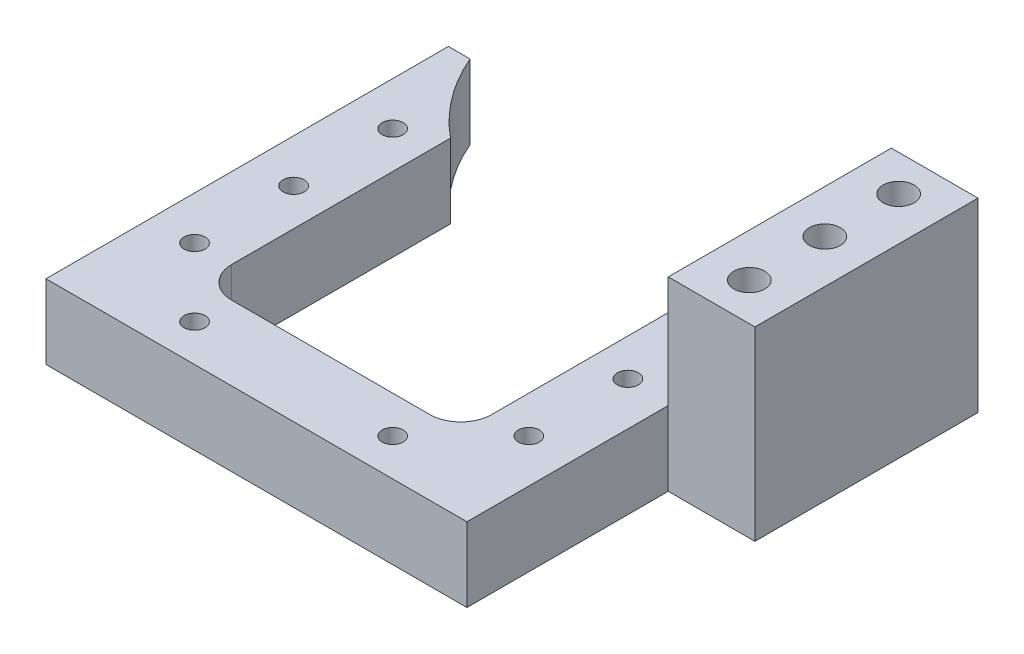
SolidWorks part; units mm, degrees
ref_plane "Front Plane" through (0, 0, 0) normal (0, 0, 1) x (1, 0, 0)
ref_plane "Top Plane" through (0, 0, 0) normal (0, 1, 0) x (1, 0, 0)
ref_plane "Right Plane" through (0, 0, 0) normal (1, 0, 0) x (0, 0, -1)
sketch "Sketch1" plane through (0, 0, 0) normal (0, 1, 0) x (1, 0, 0)
  line L0 (0, 0) -> (0, 11.5) construction
  line L1 (0, 0) -> (0, -36) construction
  line L2 (0, 0) -> (13.5, 0) construction
  line L3 (0, 0) -> (-13.5, 0) construction
  line L4 (-13.5, 0) -> (-13.5, -6.5) construction
  line L5 (-13.5, -6.5) -> (-13.5, -14.5) construction
  line L6 (-13.5, -14.5) -> (-13.5, -22.5) construction
  line L7 (-13.5, -22.5) -> (-13.5, -30.5) construction
  line L8 (-17, -6.5) -> (-17, -33.5)
  line L9 (-17, -33.5) -> (-17, -39)
  line L12 (-13.5, -30.5) -> (-13.5, -36) construction
  line L13 (-13.5, -36) -> (-8, -36) construction
  line L14 (13.5, 0) -> (13.5, -6.5) construction
  line L15 (13.5, -6.5) -> (13.5, -14.5) construction
  line L16 (13.5, -14.5) -> (13.5, -22.5) construction
  line L17 (13.5, -22.5) -> (13.5, -30.5) construction
  line L18 (13.5, -30.5) -> (13.5, -36) construction
  line L19 (13.5, -36) -> (8, -36) construction
  line L20 (-13.5, -6.5) -> (-17, -6.5) construction
  line L21 (-13.5, -6.5) -> (-10, -6.5) construction
  line L22 (13.5, -6.5) -> (10, -6.5) construction
  line L23 (13.5, -6.5) -> (17, -6.5) construction
  line L24 (17, -33.5) -> (17, -39)
  line L25 (17, -6.5) -> (17, -33.5)
  line L26 (13.5, -6.5) -> (17, -6.5) construction
  line L27 (-17, -39) -> (17, -39)
  line L28 (-17, -6.5) -> (-15.25, -6.5)
  line L29 (-10.5, -12.8282) -> (-10.5, -30.5)
  line L30 (-10.5, -30.5) -> (-8, -30.5)
  line L31 (-8, -30.5) -> (-8, -33)
  line L32 (8, -33) -> (-8, -33)
  line L33 (8, -30.5) -> (8, -33)
  line L34 (10.5, -30.5) -> (8, -30.5)
  line L35 (10.5, -12.8282) -> (10.5, -30.5)
  line L36 (17, -6.5) -> (15.25, -6.5)
  circle A0 centre (0, 0) radius 16 construction
  circle A1 centre (0, 0) radius 11 construction
  circle A2 centre (-13.5, -30.5) radius 0.85
  circle A3 centre (-13.5, -22.5) radius 0.85
  circle A4 centre (-13.5, -14.5) radius 0.85
  circle A5 centre (-8, -36) radius 0.85
  circle A6 centre (8, -36) radius 0.85
  circle A7 centre (13.5, -30.5) radius 0.85
  circle A8 centre (13.5, -22.5) radius 0.85
  circle A9 centre (13.5, -14.5) radius 0.85
  arc A10 (-15.25, -6.5) -> (-10.5, -12.8282) centre (0, 0) ccw
  arc A11 (15.25, -6.5) -> (10.5, -12.8282) centre (0, 0) cw
  point P45 (0, -33.5)
  dimension "D1" = 32
  dimension "D2" = 22
  dimension "D3" = 11.5
  dimension "D13" = 1.7
  dimension "D14" = 2.5
  dimension "D4" = 36
  dimension "D5" = 3
  dimension "D6" = 13.5
  dimension "D7" = 6.5
  dimension "D8" = 8
  dimension "D9" = 8
  dimension "D10" = 8
  dimension "D11" = 5.5
  dimension "D12" = 5.5
  dimension "D15" = 3.5
  dimension "D16" = 3.5
  dimension "D17" = 3.5
  dimension "D18" = 3
  dimension "D19" = 13.5
  dimension "D20" = 3
extrude "Boss-Extrude1" add sketch "Sketch1" along normal blind 6
sketch "Sketch2" plane through (0, 0, 0) normal (0, -1, 0) x (1, 0, 0)
  line L0 (10.5, 12.8282) -> (10.5, 17.3382) construction
  line L1 (10.5, 12.8282) -> (10.5, 30.5) construction
  line L2 (10.5, 17.3382) -> (10.5, 19.3382) construction
  circle A0 centre (10.5, 19.3382) radius 2
  dimension "D3" = 4
  dimension "D1" = 4.51
  dimension "D2" = 2
sketch "Sketch3" plane through (0, 0, 0) normal (0, -1, 0) x (1, 0, 0)
  line L0 (17, 22.74) -> (24, 22.74)
  line L3 (24, 22.74) -> (24, 4.72)
  line L4 (24, 4.72) -> (17, 4.72)
  line L5 (17, 4.72) -> (17, 7.9018)
  line L6 (17, 22.74) -> (17, 7.9018)
  dimension "D1" = 16.26
  dimension "D2" = 7
  dimension "D3" = 18.02
extrude "Boss-Extrude2" add sketch "Sketch3" against normal blind 15
sketch "Sketch4" plane through (0, 0, 0) normal (0, -1, 0) x (1, 0, 0)
  line L0 (17, 22.74) -> (17, 10.54) construction
  line L1 (17, 10.54) -> (24, 10.54) construction
  line L2 (24, 4.72) -> (24, 22.74) construction
  line L3 (24, 4.72) -> (24, 22.74) construction
  line L4 (17, 10.54) -> (17, 4.72) construction
  line L5 (24, 4.72) -> (17, 10.54) construction
  line L6 (24, 10.54) -> (17, 4.72) construction
  line L9 (24, 16.64) -> (17, 16.64) construction
  line L10 (24, 10.54) -> (17, 16.64) construction
  line L11 (17, 10.54) -> (24, 16.64) construction
  line L12 (24, 16.64) -> (17, 22.74) construction
  line L13 (17, 16.64) -> (24, 22.74) construction
  circle A0 centre (20.5, 7.63) radius 1.25
  circle A1 centre (20.5, 13.59) radius 1.25
  circle A2 centre (20.5, 19.69) radius 1.25
  dimension "D1" = 12.2
  dimension "D2" = 2.5
extrude "Cut-Extrude2" cut sketch "Sketch4" against normal through all
sketch "Sketch5" plane through (0, 0, 0) normal (0, -1, 0) x (1, 0, 0)
  line L1 (8, 30.5) -> (8, 33) construction
  line L2 (8, 33) -> (-8, 33)
  line L3 (-8, 33) -> (-8, 30.5) construction
  line L4 (-8, 30.5) -> (-10.5, 30.5) construction
  line L5 (10.5, 30.5) -> (-10.5, 30.5)
  arc A0 (10.5, 30.5) -> (8, 33) centre (8, 30.5) ccw
  arc A1 (-8, 33) -> (-10.5, 30.5) centre (-8, 30.5) ccw
extrude "Cut-Extrude3" cut sketch "Sketch5" against normal blind 10
sketch "Sketch7" plane through (0, 6, 0) normal (0, 1, 0) x (1, 0, 0)
  line L0 (17, -4.7223) -> (15.25, -4.7223)
  line L1 (15.25, -4.7223) -> (15.25, -6.5)
  line L2 (15.25, -6.5) -> (17, -6.5)
  line L3 (17, -6.5) -> (17, -4.7223)
  line L4 (24.01, -4.7223) -> (14.01, -4.7223) construction
extrude "Boss-Extrude4" add sketch "Sketch7" against normal up to surface (6 mm away) up to face at (20.5, 0, 18.44)
